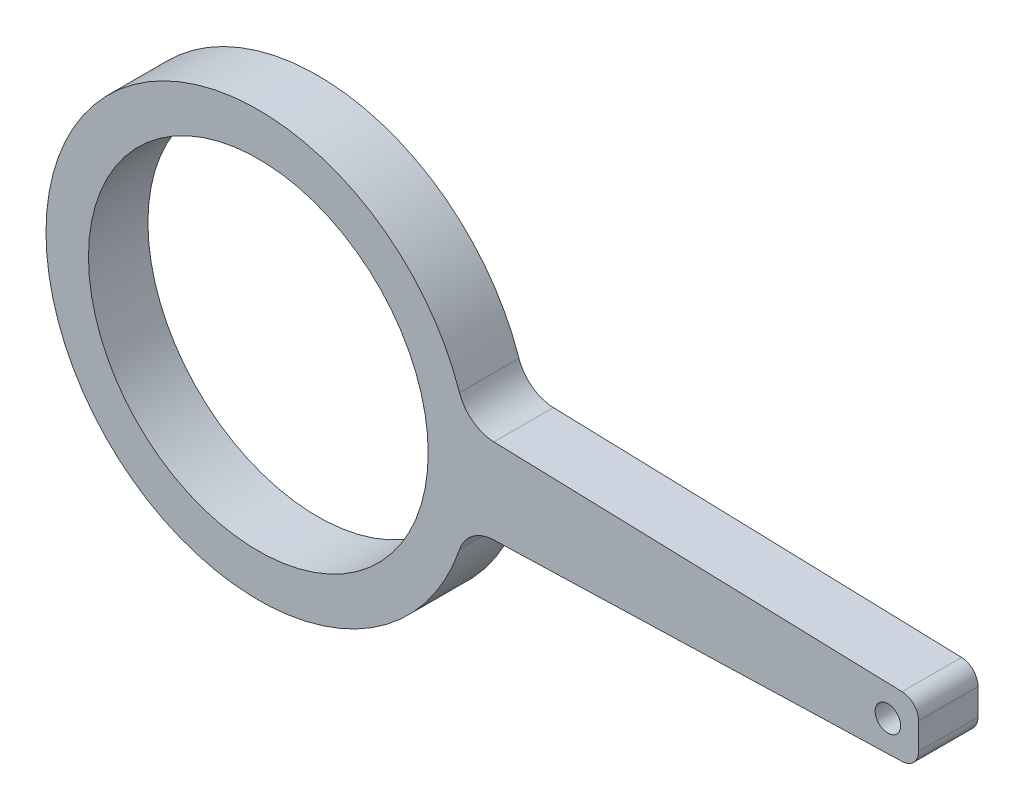
SolidWorks part; units mm, degrees
ref_plane "Front Plane" through (0, 0, 0) normal (0, 0, 1) x (1, 0, 0)
ref_plane "Top Plane" through (0, 0, 0) normal (0, 1, 0) x (1, 0, 0)
ref_plane "Right Plane" through (0, 0, 0) normal (1, 0, 0) x (0, 0, -1)
sketch "Sketch1" plane through (0, 0, 0) normal (0, 0, 1) x (1, 0, 0)
  line L0 (0, 0) -> (76.392, 0) construction
  line L4 (77.7356, -1.5591) -> (77.7356, 1.5591)
  line L5 (75.7956, 3.5582) -> (27.7356, 5)
  line L6 (74.1274, 0) -> (74.1274, 3.6082) construction
  line L7 (74.1274, 0) -> (77.7356, 0) construction
  line L8 (75.7956, -3.5582) -> (27.7356, -5)
  arc A0 (23.6854, 8) -> (23.6854, -8) centre (0, 0) ccw
  arc A7 (27.7356, 5) -> (23.6854, 8) centre (27.868, 9.4127) cw
  circle A8 centre (0, 0) radius 20
  circle A9 centre (74.1274, 0) radius 1.5
  arc A10 (77.7356, 1.5591) -> (75.7956, 3.5582) centre (75.7356, 1.5591) ccw
  arc A11 (77.7356, -1.5591) -> (75.7956, -3.5582) centre (75.7356, -1.5591) cw
  arc A12 (27.7356, -5) -> (23.6854, -8) centre (27.868, -9.4127) ccw
  point P10 (74.1274, 0)
  point P16 (77.7356, 3.5)
  dimension "D1" = 5
  dimension "D2" = 3.5
  dimension "D4" = 50
  dimension "D5" = 5
  dimension "D3" = 50
  dimension "D7" = 2
  dimension "D6" = 8
extrude "Boss-Extrude1" add sketch "Sketch1" along normal blind 7
